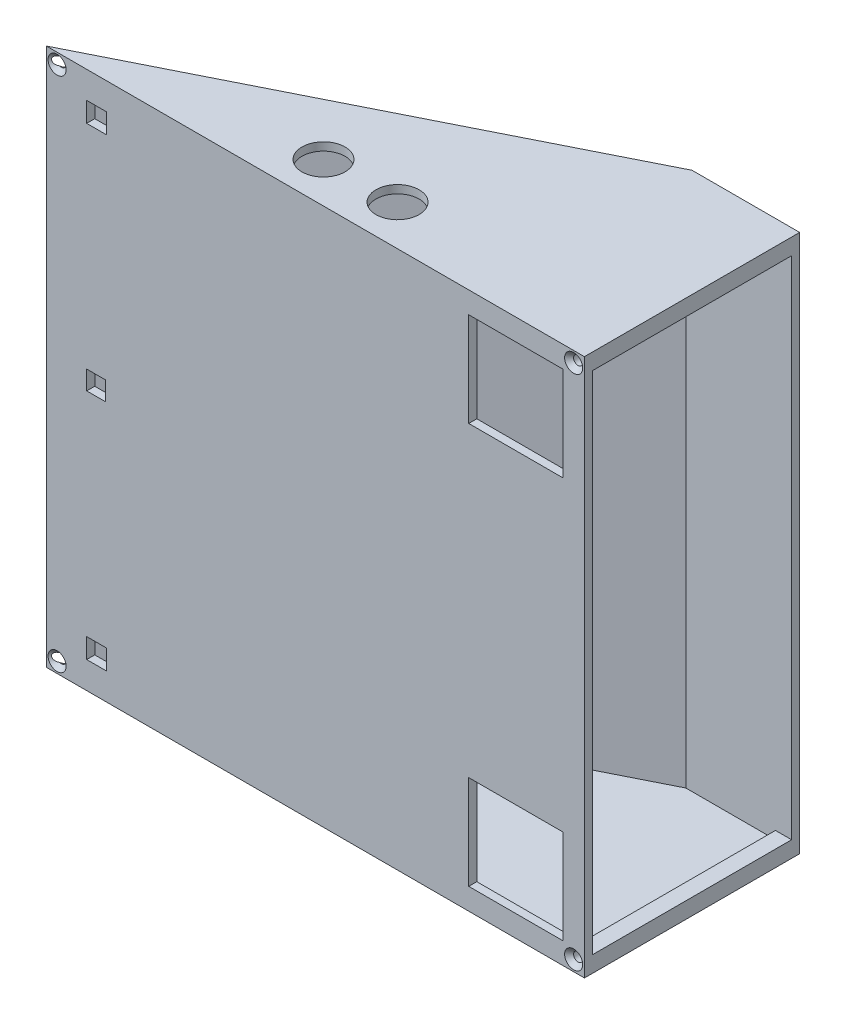
SolidWorks part; units mm, degrees
ref_plane "Alzado" through (0, 0, 0) normal (0, 0, 1) x (1, 0, 0)
ref_plane "Planta" through (0, 0, 0) normal (0, 1, 0) x (1, 0, 0)
ref_plane "Vista lateral" through (0, 0, 0) normal (1, 0, 0) x (0, 0, -1)
sketch "Croquis1" plane through (0, 0, 0) normal (0, 1, 0) x (1, 0, 0)
  line L0 (0, 0) -> (200, 0)
  line L5 (200, 0) -> (200, 80)
  line L6 (200, 80) -> (160, 80)
  line L7 (160, 80) -> (0, 0)
  dimension "D1" = 200
  dimension "D2" = 80
  dimension "D3" = 40
extrude "Saliente-Extruir2" add sketch "Croquis1" along normal blind 200
sketch "Croquis2" plane through (0, 200, 0) normal (0, 1, 0) x (1, 0, 0)
  line L0 (0, 0) -> (200, 0) construction
  circle A0 centre (88.0116, 15) radius 8.02
  circle A1 centre (115.5316, 15) radius 8.02
  dimension "D2" = 16.04
  dimension "D3" = 15
  dimension "D4" = 16.04
  dimension "D1" = 15
  dimension "D5" = 27.52
sketch "Croquis3" plane through (0, 0, -80) normal (0, 0, -1) x (-1, 0, 0)
  line L0 (-200, 0) -> (-200, 200) construction
sketch "Croquis5" plane through (0, 0, 0) normal (0, -1, 0) x (1, 0, 0)
  circle A0 centre (88.0116, -15) radius 8.02
  circle A1 centre (115.5316, -15) radius 8.02
ref_plane "Plano1" through (0, 0, 0) normal (1, 0, 0) x (0, 0, -1)
shell "Vaciado2" thickness 3
sketch "Croquis6" plane through (0, 0, 0) normal (1, 0, 0) x (0, 0, -1)
  line L1 (0, 200) -> (0, 0) construction
  line L3 (30, 88.575) -> (30, 111.425) construction
  line L4 (80, 0) -> (0, 0) construction
  circle A0 centre (30, 88.575) radius 8.2
  circle A1 centre (30, 111.425) radius 8.2
  point P2 (30, 100)
  dimension "D1" = 16.4
  dimension "D2" = 22.85
  dimension "D3" = 30
  dimension "D4" = 16.4
  dimension "D6" = 30
  dimension "D5" = 100
extrude "Cortar-Extruir4" cut sketch "Croquis6" along normal blind 80 contours A1 | A0
extrude "Cortar-Extruir5" cut sketch "Croquis2" against normal blind 3 contours A0 | A1
extrude "Cortar-Extruir6" cut sketch "Croquis5" against normal blind 3 contours A0 | A1
sketch "Croquis7" plane through (0, 0, 0) normal (0, 0, 1) x (1, 0, 0)
  line L0 (0, 0) -> (200, 0) construction
  line L1 (15, 10) -> (22.4, 10)
  line L2 (15, 10) -> (15, 17.4)
  line L3 (15, 17.4) -> (22.4, 17.4)
  line L4 (22.4, 10) -> (22.4, 17.4)
  line L5 (0, -44) -> (0, 44) construction
  point P4 (18.7, 10)
  dimension "D1" = 7.4
  dimension "D2" = 7.4
  dimension "D3" = 10
  dimension "D4" = 15
ref_plane "Plano2" through (0, 100, 0) normal (0, 1, 0) x (1, 0, 0)
extrude "Cortar-Extruir11" cut sketch "Croquis7" against normal blind 3 contours L4 L3 L2 L1
mirror "Simetría5" about plane through (0, 100, 0) normal (0, 1, 0) of "Cortar-Extruir11"
sketch "Croquis8" plane through (0, 0, 0) normal (0, 0, 1) x (1, 0, 0)
  line L0 (0, 200) -> (200, 200) construction
  line L1 (22.04, 103.52) -> (15, 103.52)
  line L2 (22.04, 103.52) -> (22.04, 96.48)
  line L3 (22.04, 96.48) -> (15, 96.48)
  line L4 (15, 103.52) -> (15, 96.48)
  line L5 (0, 0) -> (200, 0) construction
  line L7 (0, -44) -> (0, 44) construction
  point P6 (18.52, 103.52)
  point P9 (18.52, 96.48)
  dimension "D1" = 96.48
  dimension "D2" = 96.48
  dimension "D3" = 3.52
  dimension "D4" = 15
extrude "Cortar-Extruir12" cut sketch "Croquis8" against normal blind 3
sketch "Croquis9" plane through (0, 0, 0) normal (0, 0, 1) x (1, 0, 0)
  line L0 (200, 0) -> (200, 200) construction
  line L1 (192, 192) -> (157, 192)
  line L2 (192, 192) -> (192, 157)
  line L3 (192, 157) -> (157, 157)
  line L4 (157, 192) -> (157, 157)
  line L5 (0, 200) -> (200, 200) construction
  dimension "D1" = 8
  dimension "D2" = 8
  dimension "D3" = 35
  dimension "D4" = 35
extrude "Cortar-Extruir13" cut sketch "Croquis9" against normal blind 3
mirror "Simetría6" about plane through (0, 100, 0) normal (0, 1, 0) of "Cortar-Extruir13"
sketch "Croquis15" plane through (0, 0, -3) normal (0, 0, -1) x (-1, 0, 0)
  line L1 (-200, 3) -> (-194, 3)
  line L2 (-200, 3) -> (-200, 6)
  line L3 (-200, 6) -> (-194, 6)
  line L4 (-194, 3) -> (-194, 6)
  dimension "D1" = 6
  dimension "D2" = 3
extrude "Saliente-Extruir3" add sketch "Croquis15" along normal blind 75
mirror "Simetría7" about plane through (0, 100, 0) normal (0, 1, 0) of "Saliente-Extruir3"
sketch "Croquis16" plane through (0, 0, 0) normal (0, 0, 1) x (1, 0, 0)
  line L0 (0, 0) -> (200, 0) construction
  line L1 (200, 0) -> (200, 200) construction
  circle A0 centre (196, 4) radius 1.5
  dimension "D1" = 3
  dimension "D2" = 4
  dimension "D3" = 4
hole_wizard "Refrentado para tornillo tapón con cabeza plana de clavija de M33" positions "Croquis3D2" profile "Croquis18" countersink size "M3" standard "Ansi Metric"
sketch3d "Croquis3D2"
  point P0 (196, 4, 0)
sketch "Croquis18" plane through (196, 4, 0) normal (1, 0, 0) x (0, -1, 0)
  line L0 (0, 0) -> (0, 11.0215)
  line L1 (0, 11.0215) -> (1.7, 10)
  line L2 (1.7, 10) -> (1.7, 1.66)
  line L3 (1.7, 1.66) -> (3.36, 0)
  line L5 (3.36, 0) -> (0, 0)
  line L6 (-1.7, 1.66) -> (-3.36, 0) construction
  line L10 (0, 11.0215) -> (-1.7, 10) construction
  line L11 (0, -6.35) -> (0, 107.95) construction
  dimension "Diámetro de taladro" = 3.4
  dimension "Profundidad de taladro" = 10
  dimension "Ángulo de avellanado cercano" = 6.72
  dimension "Ángulo de avellanado lejano" = 90
  dimension "Ángulo de perforador" = 118
mirror "Simetría8" about plane through (0, 100, 0) normal (0, 1, 0) of "Refrentado para tornillo tapón con cabeza plana de clavija de M33"
ref_plane "Plano3" through (100, 0, 0) normal (1, 0, 0) x (0, 0, -1)
mirror "Simetría9" about plane through (100, 0, 0) normal (1, 0, 0) of "Simetría8", "Refrentado para tornillo tapón con cabeza plana de clavija de M33"
ref_plane "Plano4" through (0, 0, -3) normal (0, 0, 1) x (1, 0, 0)
